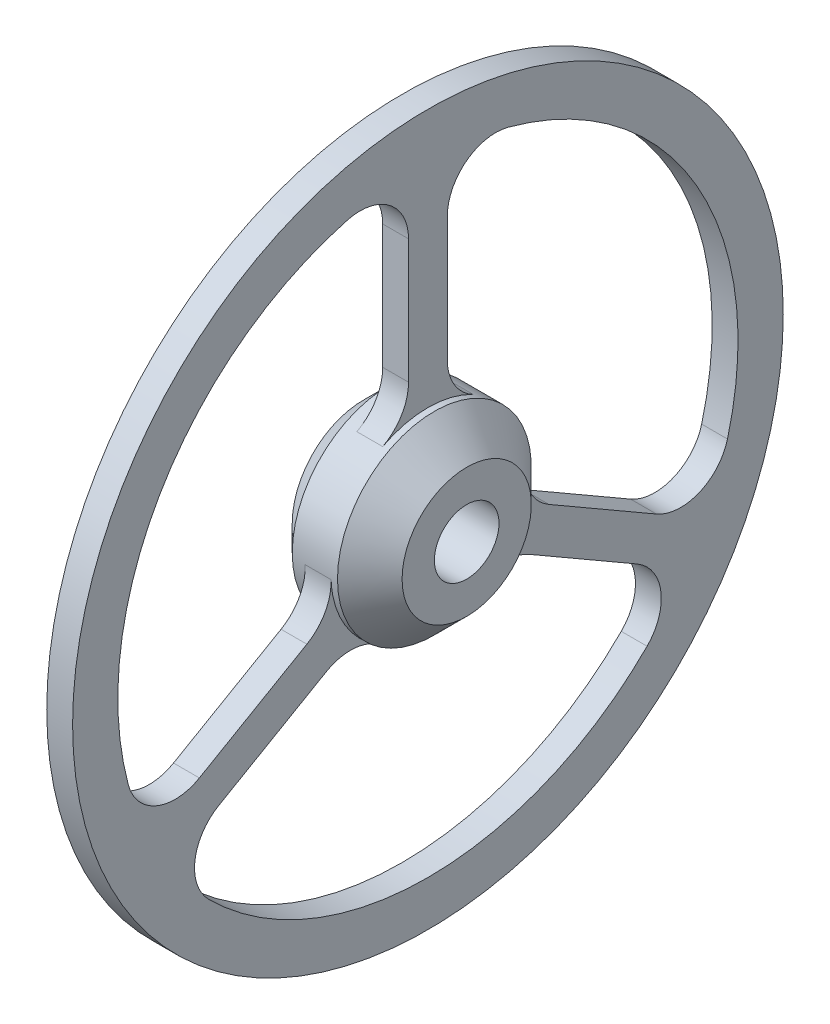
SolidWorks part; units mm, degrees
ref_plane "前视基准面" through (0, 0, 0) normal (0, 0, 1) x (1, 0, 0)
ref_plane "上视基准面" through (0, 0, 0) normal (0, 1, 0) x (1, 0, 0)
ref_plane "右视基准面" through (0, 0, 0) normal (1, 0, 0) x (0, 0, -1)
sketch "草图1" plane through (0, 0, 0) normal (1, 0, 0) x (0, 0, -1)
  line L0 (0, 80.7211) -> (0, -108.2913) construction
  line L1 (-98.3268, 0) -> (94.8953, 0) construction
  line L2 (-3, 39.1152) -> (-3, 19.8997)
  line L3 (3, 39.1152) -> (3, 19.8997)
  line L4 (35.3748, -16.9595) -> (18.7337, -7.3518)
  line L5 (32.3748, -22.1557) -> (15.7337, -12.548)
  line L6 (-32.3748, -22.1557) -> (-15.7337, -12.548)
  line L7 (-35.3748, -16.9595) -> (-18.7337, -7.3518)
  arc A0 (-7, 13.2665) -> (-14.9891, -0.5711) centre (0, 0) ccw
  circle A1 centre (0, 0) radius 55
  arc A2 (-12.4444, 46.3588) -> (-46.3701, -12.4022) centre (0, 0) ccw
  arc A3 (46.3701, -12.4022) -> (35.3748, -16.9595) centre (39.1248, -10.4643) cw
  arc A4 (12.4444, 46.3588) -> (3, 39.1152) centre (10.5, 39.1152) ccw
  arc A5 (3, 19.8997) -> (7, 13.2665) centre (10.5, 19.8997) ccw
  arc A6 (-3, 19.8997) -> (-7, 13.2665) centre (-10.5, 19.8997) cw
  arc A7 (-12.4444, 46.3588) -> (-3, 39.1152) centre (-10.5, 39.1152) cw
  arc A8 (18.7337, -7.3518) -> (14.9891, -0.5711) centre (22.4837, -0.8566) cw
  arc A9 (15.7337, -12.548) -> (7.9891, -12.6954) centre (11.9837, -19.0431) ccw
  arc A10 (33.9257, -33.9566) -> (32.3748, -22.1557) centre (28.6248, -28.6509) ccw
  arc A11 (-33.9257, -33.9566) -> (-32.3748, -22.1557) centre (-28.6248, -28.6509) cw
  arc A12 (-15.7337, -12.548) -> (-7.9891, -12.6954) centre (-11.9837, -19.0431) cw
  arc A13 (-18.7337, -7.3518) -> (-14.9891, -0.5711) centre (-22.4837, -0.8566) ccw
  arc A14 (-46.3701, -12.4022) -> (-35.3748, -16.9595) centre (-39.1248, -10.4643) ccw
  arc A15 (-7.9891, -12.6954) -> (7.9891, -12.6954) centre (0, 0) ccw
  arc A16 (-33.9257, -33.9566) -> (33.9257, -33.9566) centre (0, 0) ccw
  arc A17 (14.9891, -0.5711) -> (7, 13.2665) centre (0, 0) ccw
  arc A18 (46.3701, -12.4022) -> (12.4444, 46.3588) centre (0, 0) ccw
  point P48 (0, 0)
  point P59 (0, 0)
  dimension "D1" = 96
  dimension "D2" = 110
  dimension "D3" = 30
  dimension "D4" = 3
  dimension "D6" = 15
  dimension "D7" = 15
  dimension "D5" = 6
extrude "凸台-拉伸1" add sketch "草图1" along normal blind 4
ref_plane "基准面1" through (-6, 0, 0) normal (-1, 0, 0) x (0, 0, 1)
sketch "草图3" plane through (-6, 0, 0) normal (-1, 0, 0) x (0, 0, 1)
  circle A0 centre (0, 0) radius 15
  dimension "D1" = 30
sketch "草图4" plane through (0, 0, 0) normal (-1, 0, 0) x (0, 0, 1)
  circle A0 centre (0, 0) radius 15
loft "放样1" add profiles "草图4", "草图3"
ref_plane "基准面2" through (10, 0, 0) normal (1, 0, 0) x (0, 0, -1)
sketch "草图6" plane through (4, 0, 0) normal (1, 0, 0) x (0, 0, -1)
  circle A0 centre (0, 0) radius 15
  dimension "D2" = 30
sketch "草图7" plane through (10, 0, 0) normal (1, 0, 0) x (0, 0, -1)
  circle A0 centre (0, 0) radius 15
  dimension "D1" = 30
loft "放样2" add profiles "草图7", "草图6"
sketch "草图9" plane through (-6, 0, 0) normal (-1, 0, 0) x (0, 0, 1)
  circle A0 centre (0, 0) radius 5
  dimension "D1" = 10
extrude "切除-拉伸1" cut sketch "草图9" against normal mid plane 48
chamfer "倒角1" distance 5 angle 45 1 edges at (10, 0, -15)
chamfer "倒角2" distance 4 angle 45 1 edges at (-6, 0, 15)
